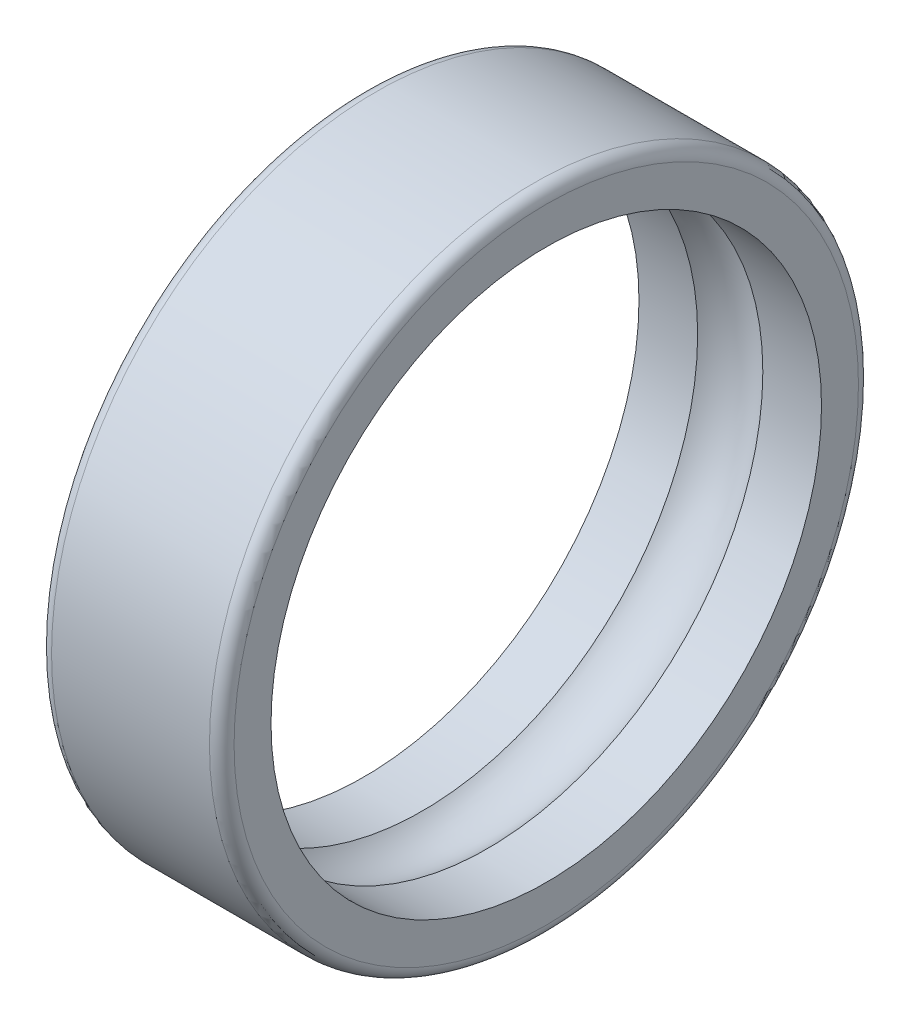
SolidWorks part; units mm, degrees
ref_plane "Plan1" through (0, 0, 0) normal (0, 0, 1) x (1, 0, 0)
ref_plane "Plan2" through (0, 0, 0) normal (0, 1, 0) x (1, 0, 0)
ref_plane "Plan3" through (0, 0, 0) normal (1, 0, 0) x (0, 0, -1)
sketch "Esquisse1" plane through (0, 0, 0) normal (0, 0, 1) x (1, 0, 0)
  line L0 (-4.5, 7.5) -> (-4.5, 16) construction
  line L1 (-3.8929, 16) -> (3.8929, 16)
  line L2 (-4.5, 15.3929) -> (-4.5, 13.5714)
  line L3 (-4.5, 13.5714) -> (-1.6063, 13.5714)
  line L4 (4.5, 15.3929) -> (4.5, 13.5714)
  line L5 (4.5, 7.5) -> (4.5, 16) construction
  line L6 (-4.5, 16) -> (4.5, 16) construction
  line L7 (1.6063, 13.5714) -> (4.5, 13.5714)
  line L8 (0, 0) -> (15, 0) construction
  line L9 (0, 0) -> (54, 0) construction
  arc A0 (3.8929, 16) -> (4.5, 15.3929) centre (3.8929, 15.3929) cw
  arc A1 (-3.8929, 16) -> (-4.5, 15.3929) centre (-3.8929, 15.3929) ccw
  arc A2 (1.6063, 13.5714) -> (-1.6063, 13.5714) centre (0, 11.75) ccw
  point P12 (4.5, 16)
  dimension "D2" = 0.6071
  dimension "D3" = 2.4286
  dimension "D1" = 2.4286
revolve "Base-Révolution" add sketch "Esquisse1" angle 360 about L8
